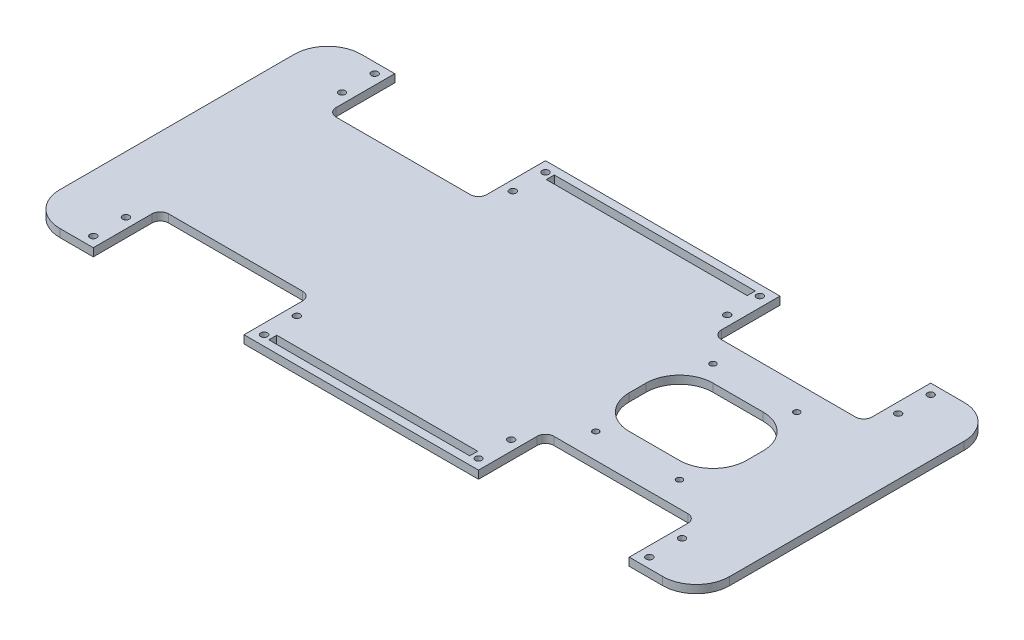
SolidWorks part; units mm, degrees
material "Pine"
ref_plane "Front Plane" through (0, 0, 0) normal (0, 0, 1) x (1, 0, 0)
ref_plane "Top Plane" through (0, 0, 0) normal (0, 1, 0) x (1, 0, 0)
ref_plane "Right Plane" through (0, 0, 0) normal (1, 0, 0) x (0, 0, -1)
sketch "Sketch1" plane through (0, 0, 0) normal (0, 1, 0) x (1, 0, 0)
  line L0 (-160, 50) -> (-160, -50) construction
  line L1 (-200, 90) -> (-160, 90)
  line L2 (-200, 90) -> (-200, -90)
  line L3 (-200, -90) -> (-160, -90)
  line L4 (200, 90) -> (200, -90)
  line L6 (-160, 90) -> (-160, 50)
  line L7 (-160, 50) -> (-70, 50)
  line L8 (-70, 90) -> (-70, 50)
  line L10 (-160, -90) -> (-160, -50)
  line L11 (-160, -50) -> (-70, -50)
  line L12 (-70, -90) -> (-70, -50)
  line L14 (70, -90) -> (70, -50)
  line L15 (70, -50) -> (160, -50)
  line L16 (160, -90) -> (160, -50)
  line L18 (70, 90) -> (70, 50)
  line L19 (70, 50) -> (160, 50)
  line L20 (160, 90) -> (160, 50)
  line L21 (-70, 50) -> (-70, -50) construction
  line L22 (70, -50) -> (-70, -50) construction
  line L23 (-70, 50) -> (70, 50) construction
  line L24 (70, -50) -> (70, 50) construction
  line L25 (-70, 90) -> (70, 90)
  line L26 (-70, -90) -> (70, -90)
  line L27 (160, -90) -> (200, -90)
  line L28 (160, 90) -> (200, 90)
  point P22 (200, 0)
  point P23 (-70, 0)
  point P24 (0, -50)
  dimension "D1" = 90
  dimension "D2" = 40
  dimension "D3" = 400
  dimension "D4" = 40
  dimension "D5" = 180
extrude "Boss-Extrude1" add sketch "Sketch1" along normal mid plane 4.7625
hole_wizard "M3 Clearance Hole1" positions "Sketch3" profile "Sketch4" hole size "M3" standard "ANSI Metric"
sketch "Sketch3" plane through (0, 2.3813, 0) normal (0, 1, 0) x (1, 0, 0)
  line L0 (85, -35) -> (135, -35) construction
  line L1 (135, -35) -> (135, 35) construction
  line L2 (135, 35) -> (85, 35) construction
  line L3 (85, 35) -> (85, -35) construction
  line L4 (85, 35) -> (135, 35)
  point P0 (135, -35)
  point P2 (85, -35)
  point P5 (85, 35)
  point P7 (135, 35)
  point P36 (0, 0)
  point P37 (0, 0)
  dimension "D1" = 50
sketch "Sketch4" plane through (135, 2.3813, 35) normal (1, 0, 0) x (0, 0, 1)
  line L0 (0, 0) -> (0, 11.0815)
  line L1 (0, 11.0815) -> (1.8, 10)
  line L2 (1.8, 10) -> (1.8, 0)
  line L5 (1.8, 0) -> (0, 0)
  line L10 (0, 11.0815) -> (-1.8, 10) construction
  line L11 (0, -6.35) -> (0, 107.95) construction
  dimension "Hole Dia." = 3.6
  dimension "Hole Depth" = 10
  dimension "Drill Angle" = 118
sketch "Sketch5" plane through (0, 2.3813, 0) normal (0, 1, 0) x (1, 0, 0)
  line L1 (-60, 85.2375) -> (60, 85.2375)
  line L2 (-60, 85.2375) -> (-60, 80.475)
  line L3 (-60, 80.475) -> (60, 80.475)
  line L4 (60, 85.2375) -> (60, 80.475)
  line L5 (-60, -80.475) -> (60, -80.475)
  line L6 (-60, -80.475) -> (-60, -85.2375)
  line L7 (-60, -85.2375) -> (60, -85.2375)
  line L8 (60, -80.475) -> (60, -85.2375)
extrude "Cut-Extrude1" cut sketch "Sketch5" against normal blind 10
sketch "Sketch6" plane through (0, -2.3813, 0) normal (0, -1, 0) x (1, 0, 0)
  line L0 (-160, 90) -> (-160, 50) construction
  line L1 (-70, 50) -> (-70, 90) construction
  line L2 (-200, 90) -> (-160, 90) construction
  line L3 (-70, -90) -> (-70, -50) construction
  line L4 (70, -90) -> (-70, -90) construction
  circle A0 centre (-166, 84) radius 2
  circle A1 centre (-166, 64.5) radius 2
  circle A2 centre (-64, 84) radius 2
  circle A3 centre (-64, 64.5) radius 2
  circle A4 centre (-166, -64.5) radius 2
  circle A5 centre (-166, -84) radius 2
  circle A6 centre (-64, -64.5) radius 2
  circle A7 centre (-64, -84) radius 2
  point P10 (0, 0)
  point P13 (0, 0)
  point P14 (0, 0)
  point P15 (-213.175, 73.9038)
  point P18 (0, 0)
  point P39 (0, 0)
  point P40 (0, 0)
  point P41 (-425.6708, -92.0385)
  dimension "D1" = 4
  dimension "D5" = 6
  dimension "D10" = 4
  dimension "D2" = 6
  dimension "D3" = 19.5
  dimension "D4" = 6
  dimension "D6" = 6
  dimension "D7" = 6
  dimension "D8" = 19.5
  dimension "D9" = 102
extrude "Cut-Extrude2" cut sketch "Sketch6" against normal blind 10
ref_plane "Plane1" through (0, 0, 0) normal (-1, 0, 0) x (0, 0, 1)
mirror "Mirror1" about plane through (0, 0, 0) normal (-1, 0, 0) of "Cut-Extrude2"
sketch "Sketch7" plane through (0, 2.3813, 0) normal (0, 1, 0) x (1, 0, 0)
  line L0 (200, -90) -> (200, 90) construction
  line L1 (75, 25) -> (145, 25)
  line L2 (75, 25) -> (75, -25)
  line L3 (75, -25) -> (145, -25)
  line L4 (145, 25) -> (145, -25)
  point P4 (75, 0)
  dimension "D1" = 70
  dimension "D2" = 50
  dimension "D3" = 55
extrude "Cut-Extrude3" cut sketch "Sketch7" against normal blind 10
fillet "Fillet1" radius 20 8 edges at (200, 0, -90) (145, 0, 25) (75, 0, 25) (75, 0, -25) (145, 0, -25) (-200, 0, -90) (-200, 0, 90) (200, 0, 90)
fillet "Fillet2" radius 5 8 edges at (70, 0, -50) (160, 0, -50) (-70, 0, -50) (-160, 0, -50) (-70, 0, 50) (-160, 0, 50) (70, 0, 50) (160, 0, 50)
